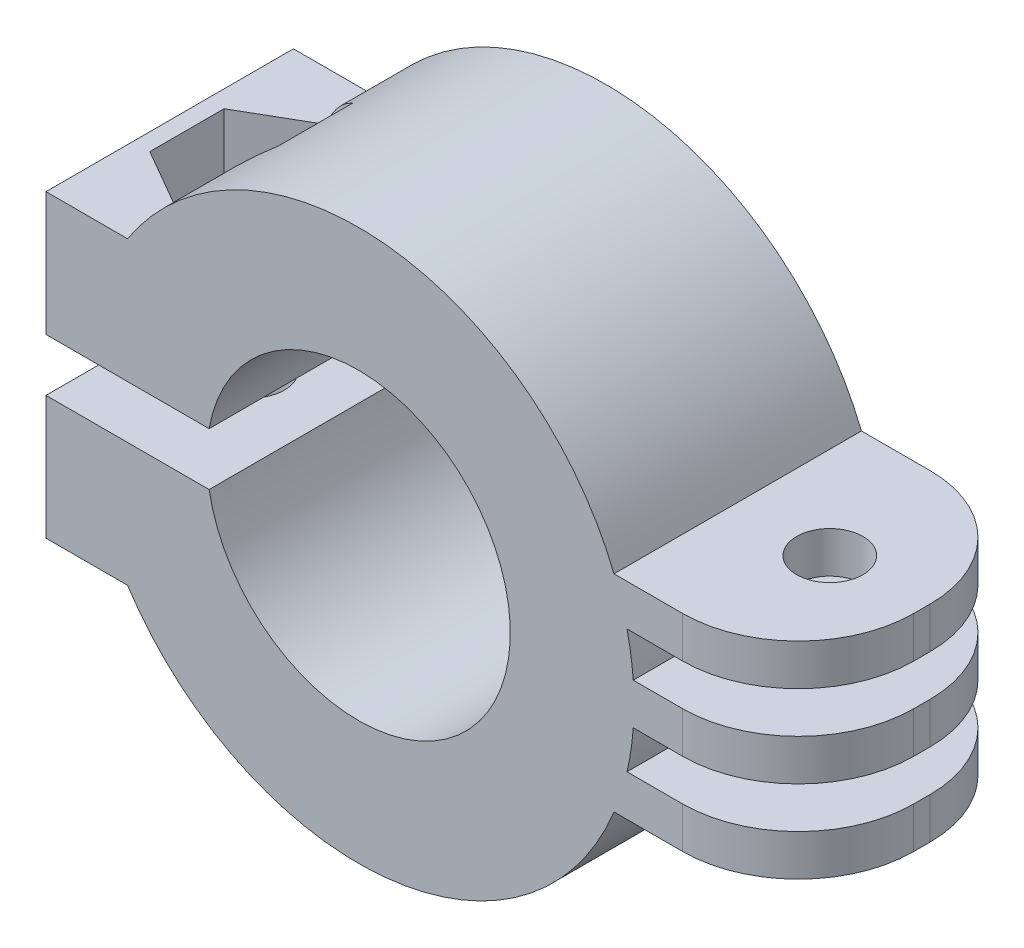
SolidWorks part; units mm, degrees
ref_plane "Front Plane" through (0, 0, 0) normal (0, 0, 1) x (1, 0, 0)
ref_plane "Top Plane" through (0, 0, 0) normal (0, 1, 0) x (1, 0, 0)
ref_plane "Right Plane" through (0, 0, 0) normal (1, 0, 0) x (0, 0, -1)
sketch "Sketch1" plane through (0, 0, 0) normal (0, 0, 1) x (1, 0, 0)
  line L0 (25.8502, 9.391) -> (25.8502, -5.2219) construction
  line L1 (0, 0) -> (-11.5065, 2.0289) construction
  line L2 (0, 0) -> (-1531.3654, 0) construction
  line L3 (-11.5065, 2.0289) -> (-24.0648, 2.0289)
  line L4 (-24.0648, 2.0289) -> (-24.0648, 11.5539)
  line L5 (-24.0648, 11.5539) -> (-17.7856, 11.5539)
  line L6 (-15.4044, -11.5539) -> (-15.4044, -2.0289) construction
  line L7 (-20.1669, 11.5539) -> (-15.4044, 11.5539) construction
  line L8 (-20.1669, 11.5539) -> (-20.1669, 2.0289) construction
  line L9 (-20.1669, 2.0289) -> (-15.4044, 2.0289) construction
  line L10 (-15.4044, 11.5539) -> (-15.4044, 2.0289) construction
  line L11 (-20.1669, -2.0289) -> (-15.4044, -2.0289) construction
  line L12 (-20.1669, -11.5539) -> (-20.1669, -2.0289) construction
  line L13 (-20.1669, -11.5539) -> (-15.4044, -11.5539) construction
  line L14 (0, 0) -> (-11.5065, -2.0289) construction
  line L15 (-24.0648, -11.5539) -> (-17.7856, -11.5539)
  line L16 (-24.0648, -2.0289) -> (-24.0648, -11.5539)
  line L17 (-11.5065, -2.0289) -> (-24.0648, -2.0289)
  line L18 (33.8495, -1.5875) -> (21.1495, -1.5875)
  line L19 (33.8495, -1.5875) -> (33.8495, 1.5875)
  line L20 (33.8495, 1.5875) -> (21.1495, 1.5875)
  line L22 (30.6127, 9.391) -> (30.6127, -5.2219) construction
  line L23 (25.8502, -5.2219) -> (30.6127, -5.2219) construction
  line L24 (25.8502, 9.391) -> (30.6127, 9.391) construction
  line L25 (20.6674, 4.7625) -> (33.8495, 4.7625)
  line L26 (33.8495, 4.7625) -> (33.8495, 7.9375)
  line L27 (33.8495, 7.9375) -> (19.6677, 7.9375)
  line L29 (33.8495, -7.9375) -> (19.6677, -7.9375)
  line L30 (33.8495, -4.7625) -> (33.8495, -7.9375)
  line L31 (20.6674, -4.7625) -> (33.8495, -4.7625)
  arc A0 (-11.5065, 2.0289) -> (0, 11.684) centre (0, 0) cw
  arc A1 (-17.7856, 11.5539) -> (-17.7856, -11.5539) centre (0, 0) cw
  arc A2 (-20.8868, 3.6829) -> (0, 21.209) centre (0, 0) cw construction
  arc A3 (-11.5065, -2.0289) -> (0, 11.684) centre (0, 0) ccw
  point P13 (-17.7856, 2.0289)
  point P14 (33.8495, 0)
  point P17 (-17.7856, 2.0289)
  point P24 (-17.7856, 11.5539)
  point P41 (32.266, 3.4713)
  point P42 (32.4526, 7.8711)
  point P43 (30.6127, 9.391)
  point P44 (33.8495, -4.7625)
  dimension "D2" = 11.684
  dimension "D4" = 9.525
  dimension "D5" = 4.7625
  dimension "D1" = 10
  dimension "D6" = 3.175
  dimension "D7" = 4.7625
  dimension "D8" = 3.175
  dimension "D9" = 12.7
  dimension "D3" = 9.525
extrude "Body" add sketch "Sketch1" along normal blind 19.05 contours A3 L17 L16 L15 A1 L5 L4 L3 A0 | L31 A1 L29 L30 | L20 A1 L18 L19 | L27 A1 L25 L26
hole_wizard "CBORE for #10 Binding Head Machine Screw1" positions "Sketch2" profile "Sketch3" counterbore size "#10" standard "ANSI Inch"
sketch "Sketch2" plane through (0, -11.5539, 0) normal (0, -1, 0) x (-1, 0, 0)
  line L0 (17.7856, -19.05) -> (17.7856, 0) construction
  point P0 (17.7856, -9.525)
sketch "Sketch3" plane through (-17.7856, -11.5539, 9.525) normal (1, 0, 0) x (0, 0, -1)
  line L0 (0, 0) -> (0, 32.7629)
  line L1 (0, 32.7629) -> (2.5527, 32.7629)
  line L3 (2.5527, 32.7629) -> (2.5527, 3.1242)
  line L4 (2.5527, 3.1242) -> (5.9436, 3.1242)
  line L5 (5.9436, 3.1242) -> (5.9436, 0)
  line L7 (5.9436, 0) -> (0, 0)
  line L11 (0, -6.35) -> (0, 107.95) construction
  dimension "Thru Hole Dia." = 5.1054
  dimension "Thru Hole Depth" = 32.7629
  dimension "C'Bore Dia." = 11.8872
  dimension "C'Bore Depth" = 3.1242
sketch "Sketch4" plane through (0, -8.4297, 0) normal (0, -1, 0) x (1, 0, 0)
  circle A1 centre (-17.7856, 9.525) radius 5.9436
  circle A2 centre (-17.7856, 9.525) radius 5.9436
  dimension "D1" = 0
extrude "#10 Head clearance" cut sketch "Sketch4" along normal through all
sketch "Sketch5" plane through (0, 11.5539, 0) normal (0, 1, 0) x (1, 0, 0)
  line L1 (-22.7386, -6.6654) -> (-22.7386, -12.3846)
  line L2 (-22.7386, -12.3846) -> (-17.7856, -15.2442)
  line L3 (-17.7856, -15.2442) -> (-12.8326, -12.3846)
  line L4 (-12.8326, -12.3846) -> (-12.8326, -6.6654)
  line L5 (-12.8326, -6.6654) -> (-17.7856, -3.8058)
  line L6 (-17.7856, -3.8058) -> (-22.7386, -6.6654)
  arc A0 (-17.7856, -6.9723) -> (-17.7856, -12.0777) centre (-17.7856, -9.525) ccw construction
  arc A1 (-17.7856, -6.9723) -> (-17.7856, -12.0777) centre (-17.7856, -9.525) ccw construction
  circle A2 centre (-17.7856, -9.525) radius 4.953 construction
  point P3 (-17.3221, -3.8246)
  line M7 (-17.7856, -19.05) -> (-17.7856, -12.0777)
  arc M8 (-17.7856, -12.0777) -> (-17.7856, -6.9723) centre (-17.7856, -9.525) cw
  line M9 (-17.7856, -6.9723) -> (-17.7856, 0)
  dimension "D1" = 9.906
extrude "#10 nut clearance" cut sketch "Sketch5" along direction (0, 1, 0) on the side against the normal blind 4.7625 and the other way through all contours L6 L1 L2 M9 M7 M8 | L4 L5 L3 M9 M8 M7
fillet "Fillet2" radius 8.89 6 edges at (33.8495, -6.35, 0) (33.8495, 0, 0) (33.8495, 6.35, 0) (33.8495, 6.35, 19.05) (33.8495, 0, 19.05) (33.8495, -6.35, 19.05)
hole_wizard "#10 Clearance Hole1" positions "Sketch7" profile "Sketch8" hole size "#10" standard "ANSI Inch" end condition through all
sketch "Sketch7" plane through (0, -7.9375, 0) normal (0, -1, 0) x (-1, 0, 0)
  line L0 (-33.8495, -9.525) -> (-19.6677, -9.525) construction
  line L1 (-33.8495, -10.16) -> (-33.8495, -8.89) construction
  line L2 (-19.6677, -19.05) -> (-19.6677, 0) construction
  point P9 (-26.7586, -9.525)
sketch "Sketch8" plane through (26.7586, -7.9375, 9.525) normal (1, 0, 0) x (0, 0, -1)
  line L0 (0, 0) -> (0, 29.1465)
  line L1 (0, 29.1465) -> (2.5527, 29.1465)
  line L2 (2.5527, 29.1465) -> (2.5527, 0)
  line L5 (2.5527, 0) -> (0, 0)
  line L11 (0, -6.35) -> (0, 107.95) construction
  dimension "Thru Hole Dia." = 5.1054
  dimension "Thru Hole Depth" = 29.1465
equation "\"D2@Sketch1\"= \"yagi_diam\" / 2 + \"tol\""
equation "\"yagi_diam\"= 0.88"
equation "\"tol\" = 0.02"
equation "\"D1@Sketch5\"=0.37+\"tol\""
